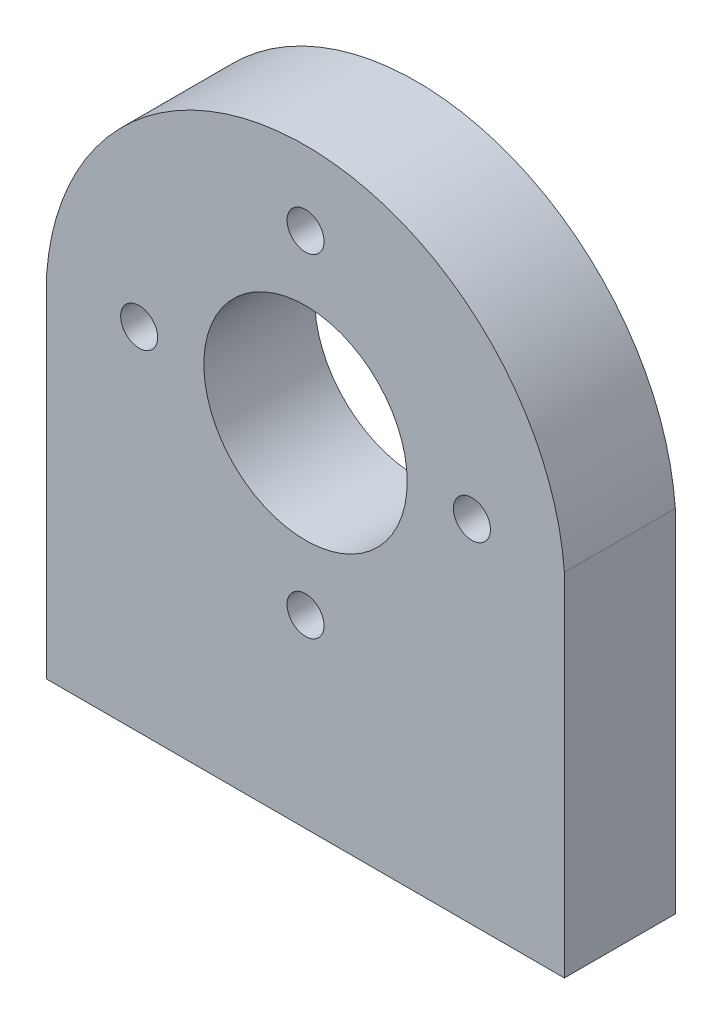
SolidWorks part; units mm, degrees
ref_plane "Front" through (0, 0, 0) normal (0, 0, 1) x (1, 0, 0)
ref_plane "Top" through (0, 0, 0) normal (0, 1, 0) x (1, 0, 0)
ref_plane "Right" through (0, 0, 0) normal (1, 0, 0) x (0, 0, -1)
sketch "Esquisse1" plane through (0, 0, 0) normal (0, 0, 1) x (1, 0, 0)
  line L1 (0, 0) -> (28, 0)
  line L2 (0, 0) -> (0, 32)
  line L3 (0, 32) -> (28, 32)
  line L4 (28, 0) -> (28, 32)
  dimension "D1" = 28
  dimension "D2" = 32
extrude "Boss.-Extru.1" add sketch "Esquisse1" along normal blind 6
sketch "Esquisse2" plane through (0, 0, 0) normal (0, -1, 0) x (1, 0, 0)
  line L0 (0, 3) -> (24.8385, 3) construction
  line L1 (0, 6) -> (0, 0) construction
  line L2 (14, 0) -> (14, 4.923) construction
  line L3 (0, 0) -> (28, 0) construction
  circle A0 centre (6, 3) radius 1.25
  circle A1 centre (22, 3) radius 1.25
  dimension "D1" = 16
  dimension "D2" = 2.5
extrude "Enlèv. mat.-Extru.1" cut sketch "Esquisse2" against normal blind 10
sketch "Esquisse3" plane through (0, 0, 6) normal (0, 0, 1) x (1, 0, 0)
  line L0 (14, 0) -> (14, 19) construction
  line L1 (0, 0) -> (28, 0) construction
  circle A0 centre (14, 19) radius 5.5
  dimension "D1" = 11
  dimension "D2" = 19
extrude "Enlèv. mat.-Extru.2" cut sketch "Esquisse3" against normal through all
sketch "Esquisse4" plane through (0, 0, 6) normal (0, 0, 1) x (1, 0, 0)
  line L0 (14, 19) -> (14, 10) construction
  circle A0 centre (14, 10) radius 1
  circle A1 centre (5, 19) radius 1
  circle A2 centre (14, 28) radius 1
  circle A3 centre (23, 19) radius 1
  point P4 (4.2258, 25.9095)
  point P5 (14, 25)
  point P13 (14, 19)
  dimension "D1" = 2
  dimension "D2" = 9
  dimension "D3" = 4
extrude "Enlèv. mat.-Extru.4" cut sketch "Esquisse4" against normal through all
sketch "Esquisse5" plane through (0, 0, 6) normal (0, 0, 1) x (1, 0, 0)
  line L0 (0, 32) -> (0, 0) construction
  line L1 (28, 0) -> (28, 32) construction
  line L2 (14, 32) -> (28, 32) construction
  line L3 (0, 19) -> (28, 19) construction
  line L4 (0, 19) -> (14, 19) construction
  line L5 (0, 19) -> (0, 33)
  line L6 (0, 33) -> (28, 33)
  line L7 (28, 33) -> (28, 19)
  arc A0 (0, 19) -> (28, 19) centre (14, 17.9615) cw
  dimension "D1" = 1
extrude "Enlèv. mat.-Extru.5" cut sketch "Esquisse5" against normal through all
